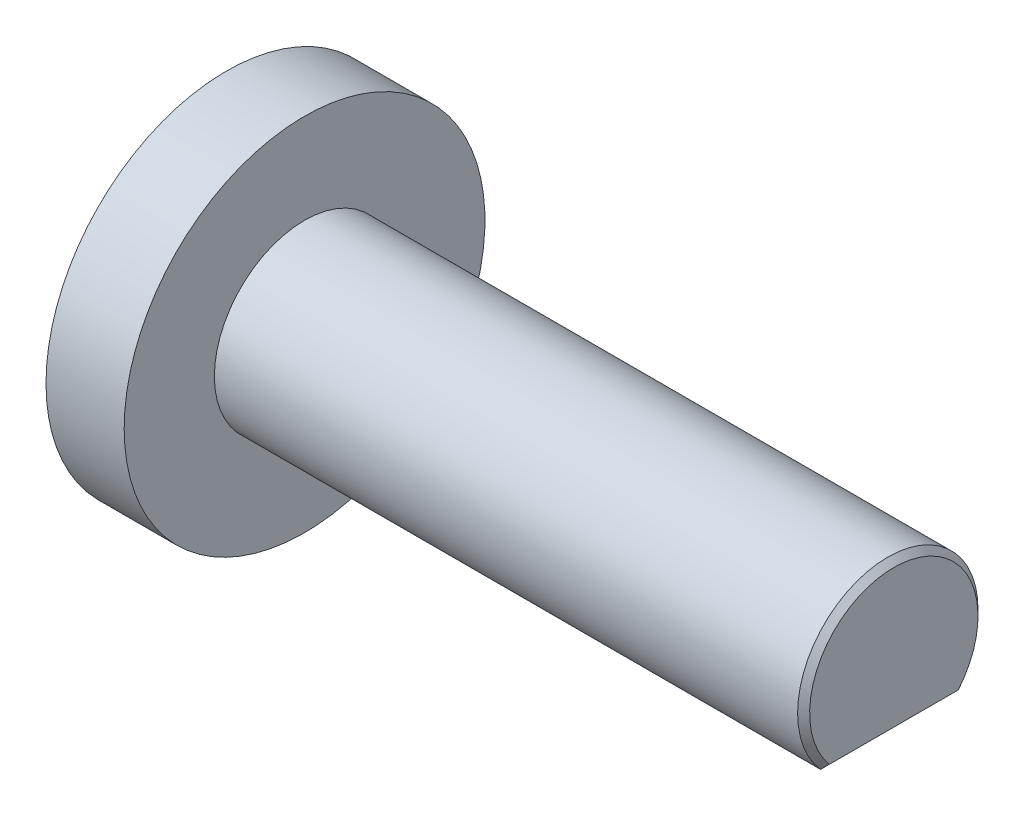
SolidWorks part; units mm, degrees
material "Unlegierter Baustahl"
ref_plane "Ebene vorne" through (0, 0, 0) normal (0, 0, 1) x (1, 0, 0)
ref_plane "Ebene oben" through (0, 0, 0) normal (0, 1, 0) x (1, 0, 0)
ref_plane "Ebene rechts" through (0, 0, 0) normal (1, 0, 0) x (0, 0, -1)
sketch "Skizze1" plane through (0, 0, 0) normal (0, 0, 1) x (1, 0, 0)
  line L0 (0, 0) -> (11.1, 0) construction
  line L1 (0, 0) -> (0, 3)
  line L2 (0, 3) -> (1.3, 3)
  line L3 (1.3, 3) -> (1.3, 1.5)
  line L4 (1.3, 1.5) -> (11.1, 1.5)
  line L5 (11.1, 1.5) -> (11.1, 0)
  line L6 (0, 0) -> (11.1, 0)
  dimension "D1" = 1.3
  dimension "D2" = 3
  dimension "D3" = 9.8
  dimension "D4" = 6
revolve "Rotation1" add sketch "Skizze1" angle 360 about L0
sketch "Skizze2" plane through (11.1, 0, 0) normal (1, 0, 0) x (0, 0, -1)
  line L1 (-1.118, -1) -> (1.118, -1)
  line L2 (-1.118, -1) -> (-1.118, -1.5)
  line L3 (-1.118, -1.5) -> (1.118, -1.5)
  line L4 (1.118, -1) -> (1.118, -1.5)
  circle A0 centre (0, 0) radius 1.5 construction
  point P6 (0, 0)
  dimension "D1" = 1
extrude "Schnitt-Linear austragen1" cut sketch "Skizze2" against normal blind 9
chamfer "Fase1" distance 0.1 angle 45 2 edges at (11.1, 1.5, 0) (11.1, -1, 0)
